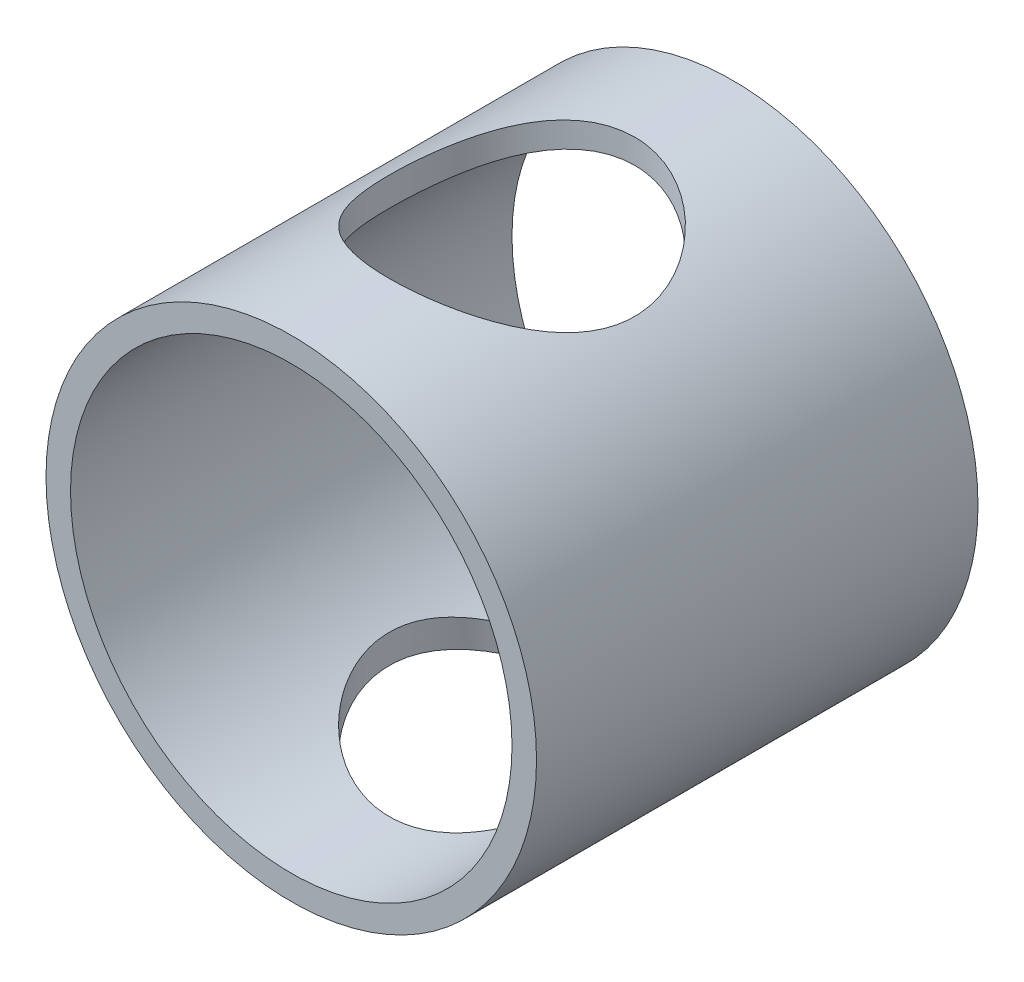
SolidWorks part; units mm, degrees
ref_plane "Alzado" through (0, 0, 0) normal (0, 0, 1) x (1, 0, 0)
ref_plane "Planta" through (0, 0, 0) normal (0, 1, 0) x (1, 0, 0)
ref_plane "Vista lateral" through (0, 0, 0) normal (1, 0, 0) x (0, 0, -1)
sketch "Croquis1" plane through (0, 0, 0) normal (0, 0, 1) x (1, 0, 0)
  circle A0 centre (0, 0) radius 28.575
  circle A1 centre (0, 0) radius 31.75
  dimension "D1" = 57.15
  dimension "D2" = 3.175
extrude "Saliente-Extruir1" add sketch "Croquis1" along normal blind 57.15
sketch "Croquis2" plane through (0, 0, 0) normal (0, 1, 0) x (1, 0, 0)
  line L0 (0, 0) -> (0, -28.575) construction
  line L1 (0, -28.575) -> (0, -57.15) construction
  circle A0 centre (0, -28.575) radius 15.875
  dimension "D1" = 31.75
  dimension "D2" = 57.15
extrude "Cortar-Extruir1" cut sketch "Croquis2" along normal through all both and the other way through all
